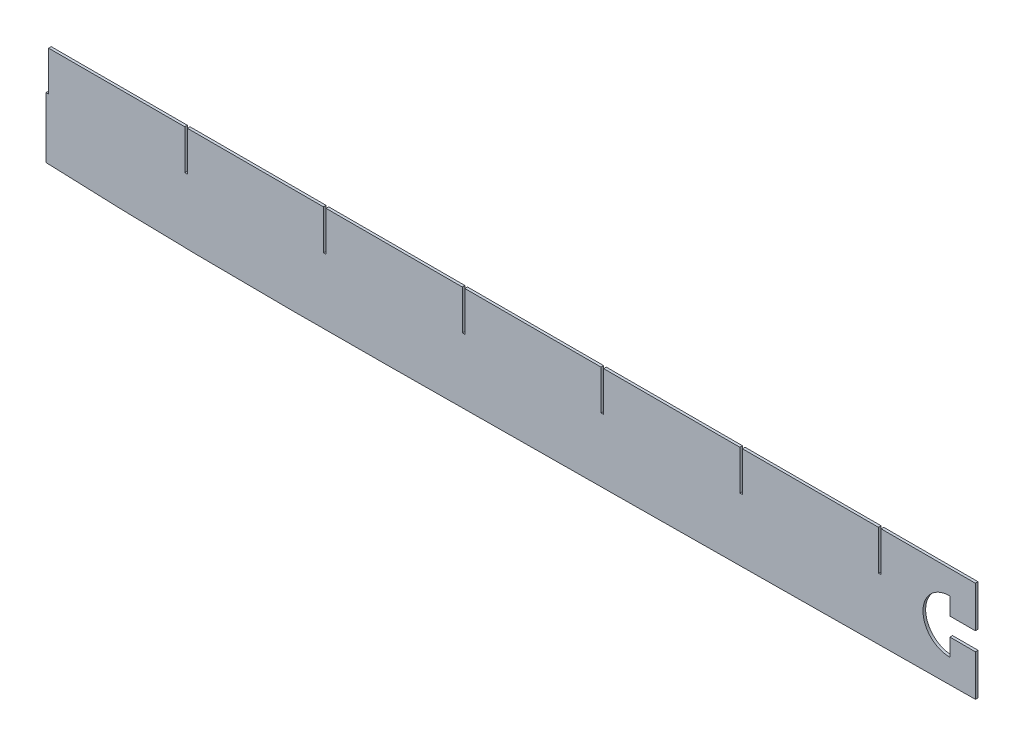
SolidWorks part; units mm, degrees
ref_plane "Front Plane" through (0, 0, 0) normal (0, 0, 1) x (1, 0, 0)
ref_plane "Top Plane" through (0, 0, 0) normal (0, 1, 0) x (1, 0, 0)
ref_plane "Right Plane" through (0, 0, 0) normal (1, 0, 0) x (0, 0, -1)
sketch "Model" plane through (0, 0, 0) normal (0, 0, 1) x (1, 0, 0)
  line L0 (1159.8, -200.4227) -> (1159.8, -247.6527)
  line L1 (1159.8, -200.4227) -> (1051.901, -200.4227)
  line L2 (1051.901, -245.9797) -> (1051.901, -200.4227)
  line L3 (1051.901, -245.9797) -> (1048.901, -245.9797)
  line L4 (1048.901, -200.4227) -> (1048.901, -245.9797)
  line L5 (1048.901, -200.4227) -> (892.901, -200.4227)
  line L6 (892.901, -245.9797) -> (892.901, -200.4227)
  line L7 (892.901, -245.9797) -> (889.901, -245.9797)
  line L8 (889.901, -200.4227) -> (889.901, -245.9797)
  line L9 (889.901, -200.4227) -> (733.901, -200.4227)
  line L10 (733.901, -245.9797) -> (733.901, -200.4227)
  line L11 (733.901, -245.9797) -> (730.901, -245.9797)
  line L12 (730.901, -200.4227) -> (730.901, -245.9797)
  line L13 (730.901, -200.4227) -> (574.901, -200.4227)
  line L14 (574.901, -245.9797) -> (574.901, -200.4227)
  line L15 (574.901, -245.9797) -> (571.901, -245.9797)
  line L16 (571.901, -200.4227) -> (571.901, -245.9797)
  line L17 (571.901, -200.4227) -> (415.901, -200.4227)
  line L18 (415.901, -245.9797) -> (415.901, -200.4227)
  line L19 (415.901, -245.9797) -> (412.901, -245.9797)
  line L20 (412.901, -200.4227) -> (412.901, -245.9797)
  line L21 (412.901, -200.4227) -> (256.901, -200.4227)
  line L22 (256.901, -245.9797) -> (256.901, -200.4227)
  line L23 (256.901, -245.9797) -> (253.901, -245.9797)
  line L24 (253.901, -200.4227) -> (253.901, -245.9797)
  line L25 (253.901, -200.4227) -> (97.901, -200.4227)
  line L26 (97.901, -245.9797) -> (97.901, -200.4227)
  line L27 (97.901, -245.9797) -> (94.901, -245.9797)
  line L28 (94.901, -315.4413) -> (94.901, -245.9797)
  line L29 (1159.8, -315.6827) -> (1159.8, -268.4527)
  line L30 (1130.6, -268.4527) -> (1159.8, -268.4527)
  line L31 (1130.6, -288.45) -> (1130.6, -268.4527)
  line L32 (1130.6, -247.6527) -> (1130.6, -227.6553)
  line L33 (1130.6, -247.6527) -> (1159.8, -247.6527)
  arc A0 (1130.6, -227.6553) -> (1130.6, -288.45) centre (1130.2, -258.0527) ccw
  spline S0 degree 3 poles (1159.8, -315.6827) (982.2995, -317.0543) (804.8009, -318.7143) (449.7983, -321.1628) (272.2336, -323.7264) (94.901, -315.4413) knots 0 0 0 0 0.5 0.5 1 1 1 1
extrude "Boss-Extrude1" add sketch "Model" along normal blind 3
